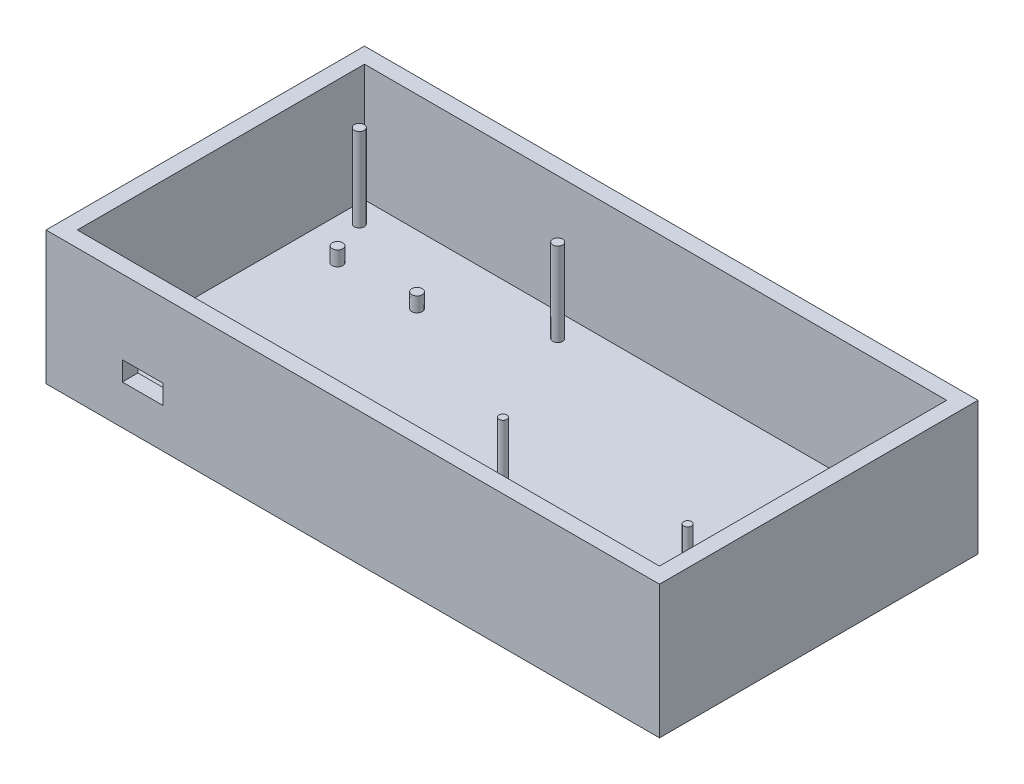
SolidWorks part; units mm, degrees
ref_plane "Plano frontal" through (0, 0, 0) normal (0, 0, 1) x (1, 0, 0)
ref_plane "Plano superior" through (0, 0, 0) normal (0, 1, 0) x (1, 0, 0)
ref_plane "Plano direito" through (0, 0, 0) normal (1, 0, 0) x (0, 0, -1)
sketch "Esboço" plane through (0, 0, 0) normal (0, 1, 0) x (1, 0, 0)
  line L1 (-92.3574, 48.2848) -> (19.1426, 48.2848)
  line L2 (-92.3574, 48.2848) -> (-92.3574, -6.7152)
  line L3 (-92.3574, -6.7152) -> (19.1426, -6.7152)
  line L4 (19.1426, 48.2848) -> (19.1426, -6.7152)
extrude "Ressalto-extrusão1" add sketch "Esboço" along normal blind 22.5
shell "Casca3" thickness 3
sketch "Esboço12" plane through (0, 0, 0) normal (0, 1, 0) x (1, 0, 0)
  circle A0 centre (-88.8574, 43.7848) radius 0.95
  circle A1 centre (-88.8574, -2.2152) radius 0.95
  circle A2 centre (-50.8574, -2.2152) radius 0.95
  circle A3 centre (-50.8574, 43.7848) radius 0.95
extrude "Ressalto-extrusão2" add sketch "Esboço12" along normal blind 16 contours A3 | A0 | A1 | A2
sketch "Esboço15" plane through (0, 0, 9.7152) normal (0, 0, 1) x (1, 0, 0)
  line L1 (-80.7474, 8.29) -> (-72.9474, 8.29)
  line L2 (-80.7474, 8.29) -> (-80.7474, 4.59)
  line L3 (-80.7474, 4.59) -> (-72.9474, 4.59)
  line L4 (-72.9474, 8.29) -> (-72.9474, 4.59)
  line L6 (-95.3574, 22.5) -> (-95.3574, -3) construction
  line L7 (-95.3574, -3) -> (22.1426, -3) construction
  dimension "D1" = 3.7
  dimension "D2" = 7.8
  dimension "D3" = 14.61
  dimension "D4" = 7.59
extrude "usb" cut sketch "Esboço15" against normal blind 3.9
sketch "Esboço16" plane through (0, 0, 0) normal (0, 1, 0) x (1, 0, 0)
  circle A0 centre (-84.5176, -5.3679) radius 1
  circle A1 centre (-69.2776, -5.3679) radius 1
  circle A2 centre (-69.2776, 35.2721) radius 1
  circle A3 centre (-84.5176, 35.2721) radius 1
extrude "Ressalto-extrusão4" add sketch "Esboço16" along normal blind 2.81 contours A3 | A2 | A1 | A0
sketch "Esboço17" plane through (0, 0, 0) normal (0, 1, 0) x (1, 0, 0)
  line L0 (19.1426, 12.8948) -> (4.9126, 12.8948) construction
  line L1 (19.1426, -6.7152) -> (19.1426, 48.2848) construction
  line L2 (4.9126, -6.7152) -> (4.9126, -4.4152) construction
  line L4 (-92.3574, -6.7152) -> (19.1426, -6.7152) construction
  line L5 (4.9126, 12.8948) -> (-30.4474, 12.8948) construction
  line L6 (-30.4474, -6.7152) -> (-30.4474, -4.4152) construction
  line L7 (-92.3574, -6.7152) -> (19.1426, -6.7152) construction
  circle A0 centre (-30.4474, 12.8948) radius 0.74
  circle A1 centre (4.9126, 12.8948) radius 0.74
  circle A2 centre (4.9126, -4.4152) radius 0.74
  circle A3 centre (-30.4474, -4.4152) radius 0.74
  dimension "D4" = 1.48
  dimension "D1" = 14.23
  dimension "D2" = 2.3
  dimension "D3" = 35.36
  dimension "D5" = 17.31
extrude "Ressalto-extrusão5" add sketch "Esboço17" along normal blind 12.6 from surface at 0 starting at face at (-84.5176, 0, 6.3679)
